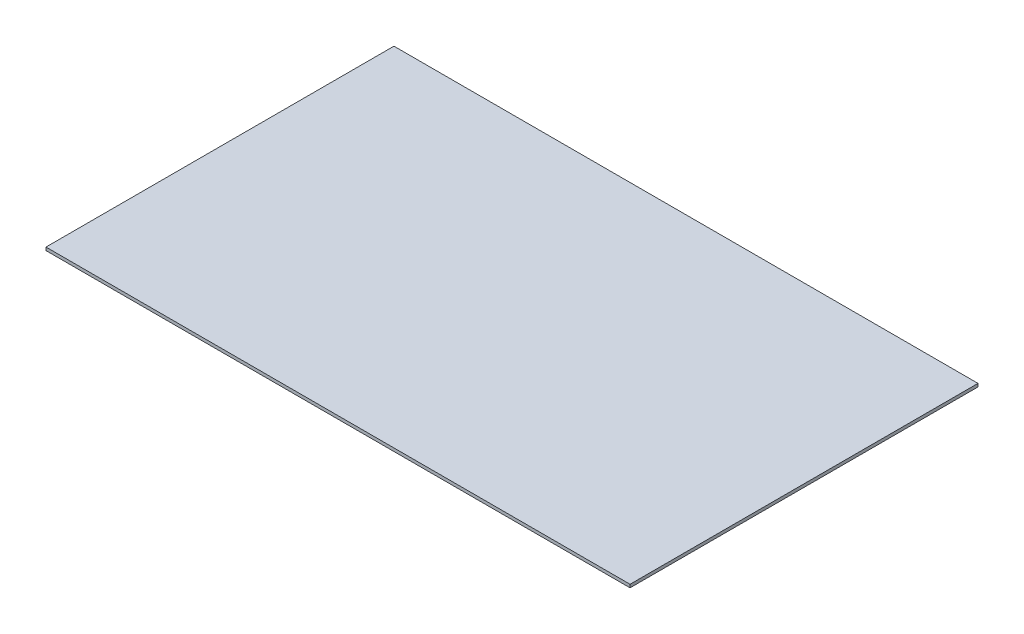
SolidWorks part; units mm, degrees
ref_plane "Front Plane" through (0, 0, 0) normal (0, 0, 1) x (1, 0, 0)
ref_plane "Top Plane" through (0, 0, 0) normal (0, 1, 0) x (1, 0, 0)
ref_plane "Right Plane" through (0, 0, 0) normal (1, 0, 0) x (0, 0, -1)
sketch "Sketch1" plane through (0, 0, 0) normal (0, 1, 0) x (1, 0, 0)
  line L1 (0, 0) -> (596.9, 0)
  line L2 (0, 0) -> (0, -355.6)
  line L3 (0, -355.6) -> (596.9, -355.6)
  line L4 (596.9, 0) -> (596.9, -355.6)
  dimension "D1" = 596.9
  dimension "D2" = 355.6
extrude "Boss-Extrude1" add sketch "Sketch1" along normal blind 3.175
